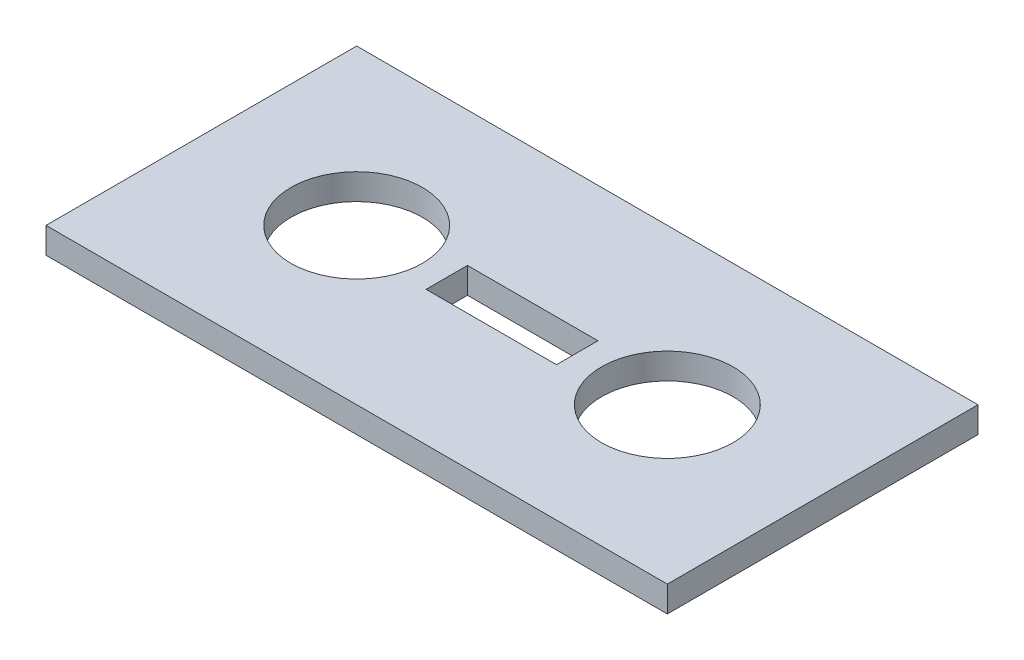
SolidWorks part; units mm, degrees
ref_plane "Front Plane" through (0, 0, 0) normal (0, 0, 1) x (1, 0, 0)
ref_plane "Top Plane" through (0, 0, 0) normal (0, 1, 0) x (1, 0, 0)
ref_plane "Right Plane" through (0, 0, 0) normal (1, 0, 0) x (0, 0, -1)
sketch "Sketch1" plane through (0, 0, 0) normal (0, 1, 0) x (1, 0, 0)
  line L0 (0, 0) -> (3.81, 0)
  line L1 (0, 0) -> (-3.81, 0)
  line L2 (-3.81, 0) -> (-3.81, 1.905)
  line L3 (-3.81, 0) -> (-3.81, -1.905)
  line L5 (-3.81, 1.905) -> (3.81, 1.905)
  line L6 (-3.81, 1.905) -> (-3.81, -1.905)
  line L7 (-3.81, -1.905) -> (3.81, -1.905)
  line L8 (3.81, 1.905) -> (3.81, -1.905)
  line L9 (-3.81, 1.905) -> (3.81, -1.905) construction
  line L10 (-3.81, -1.905) -> (3.81, 1.905) construction
  line L11 (-0.8, 0.254) -> (0.8, 0.254)
  line L12 (-0.8, 0.254) -> (-0.8, -0.254)
  line L13 (-0.8, -0.254) -> (0.8, -0.254)
  line L14 (0.8, 0.254) -> (0.8, -0.254)
  line L15 (-0.8, 0.254) -> (0.8, -0.254) construction
  line L16 (-0.8, -0.254) -> (0.8, 0.254) construction
  circle A0 centre (-1.905, 0) radius 0.16
  circle A1 centre (1.905, 0) radius 0.1685
extrude "Boss-Extrude1" add sketch "Sketch1" along normal blind 0.3175 contours A1 L0 L8 L5 L2 L1 A0 L12 L11 L14 | A1 L0 L14 L13 L12 L1 A0 L3 L7 L8
hole_wizard "#0 Clearance Hole1" positions "3DSketch1" profile "Sketch2" hole size "#0" standard "ANSI Inch"
sketch3d "3DSketch1"
  line L0 (-1.905, 0.3175, 0) -> (-1.905, 0, 0) construction
  line L1 (1.905, 0.3175, 0) -> (1.905, 0, 0) construction
  point P0 (-1.905, 0.3175, 0)
  point P4 (1.905, 0.3175, 0)
sketch "Sketch2" plane through (-1.905, 0.3175, 0) normal (1, 0, 0) x (0, 0, 1)
  line L0 (0, 0) -> (0, 7.0267)
  line L1 (0, 7.0267) -> (0.8064, 6.35)
  line L2 (0.8064, 6.35) -> (0.8064, 0)
  line L5 (0.8064, 0) -> (0, 0)
  line L10 (0, 7.0267) -> (-0.8064, 6.35) construction
  line L11 (0, -6.35) -> (0, 107.95) construction
  dimension "Hole Dia." = 1.6129
  dimension "Hole Depth" = 6.35
  dimension "Drill Angle" = 100
